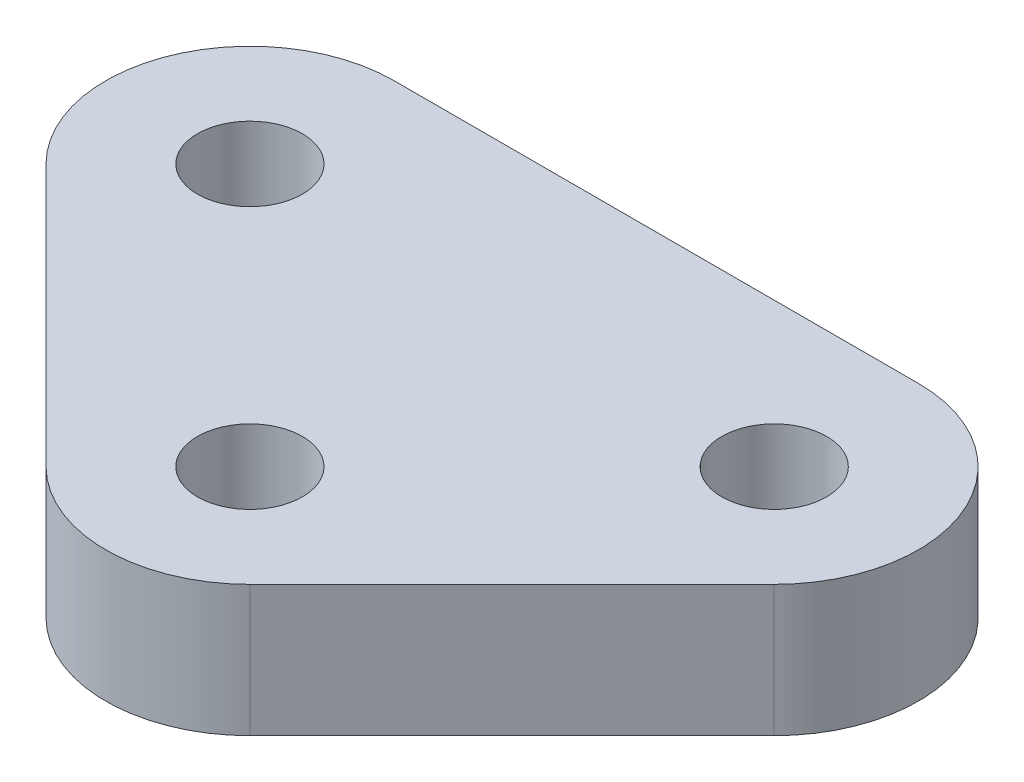
SolidWorks part; units mm, degrees
ref_plane "Front Plane" through (0, 0, 0) normal (0, 0, 1) x (1, 0, 0)
ref_plane "Top Plane" through (0, 0, 0) normal (0, 1, 0) x (1, 0, 0)
ref_plane "Right Plane" through (0, 0, 0) normal (1, 0, 0) x (0, 0, -1)
sketch "Sketch1" plane through (0, 0, 0) normal (0, 1, 0) x (1, 0, 0)
  line L0 (-10, 5.5) -> (10, 5.5)
  line L1 (13.8891, -3.8891) -> (3.8891, -13.8891)
  line L2 (-3.8891, -13.8891) -> (-13.8891, -3.8891)
  circle A0 centre (-10, 0) radius 2
  circle A1 centre (10, 0) radius 2
  circle A2 centre (0, -10) radius 2
  arc A3 (10, 5.5) -> (13.8891, -3.8891) centre (10, 0) cw
  arc A4 (3.8891, -13.8891) -> (-3.8891, -13.8891) centre (0, -10) cw
  arc A5 (-13.8891, -3.8891) -> (-10, 5.5) centre (-10, 0) cw
  point P16 (0, 0)
  point P17 (0, 0)
  point P18 (4.4841, -14.1236)
  dimension "D1" = 10
  dimension "D2" = 10
  dimension "D4" = 4
  dimension "D5" = 3.5
  dimension "D3" = 10
extrude "Boss-Extrude1" add sketch "Sketch1" along normal blind 5
